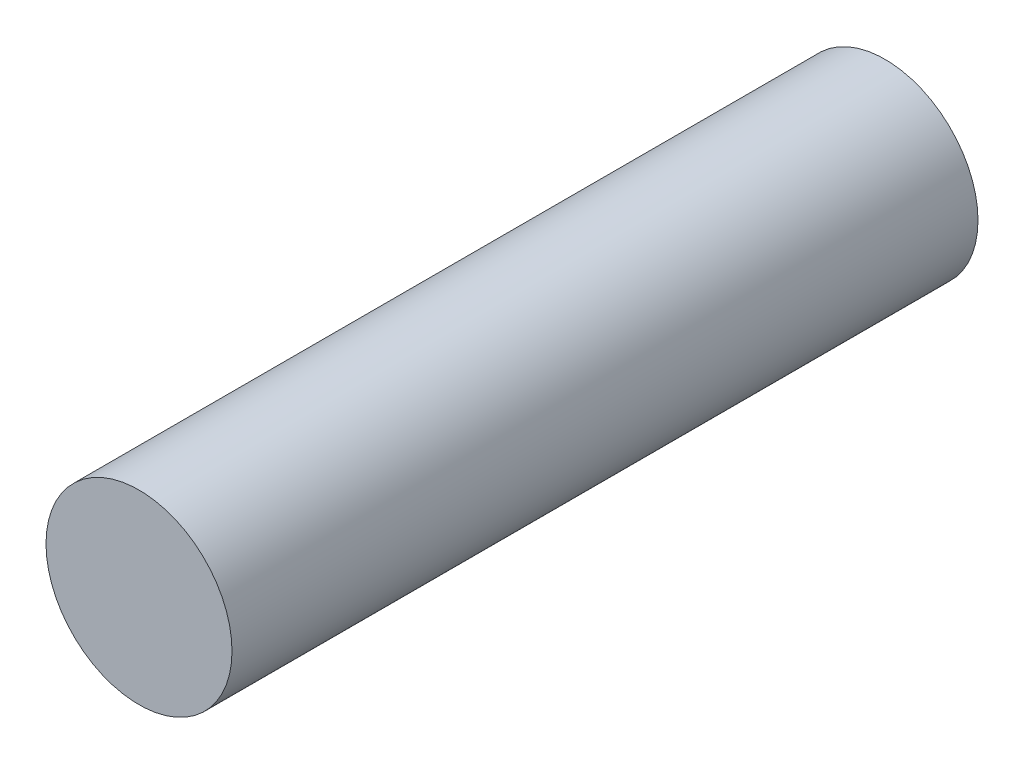
SolidWorks part; units mm, degrees
material "Plain Carbon Steel"
ref_plane "Front Plane" through (0, 0, 0) normal (0, 0, 1) x (1, 0, 0)
ref_plane "Top Plane" through (0, 0, 0) normal (0, 1, 0) x (1, 0, 0)
ref_plane "Right Plane" through (0, 0, 0) normal (1, 0, 0) x (0, 0, -1)
sketch "Sketch1" plane through (0, 0, 0) normal (0, 0, 1) x (1, 0, 0)
  circle A0 centre (-162.9182, -13.5765) radius 2.3749
  dimension "D1" = 4.7498
extrude "Boss-Extrude1" add sketch "Sketch1" along normal blind 19.05
